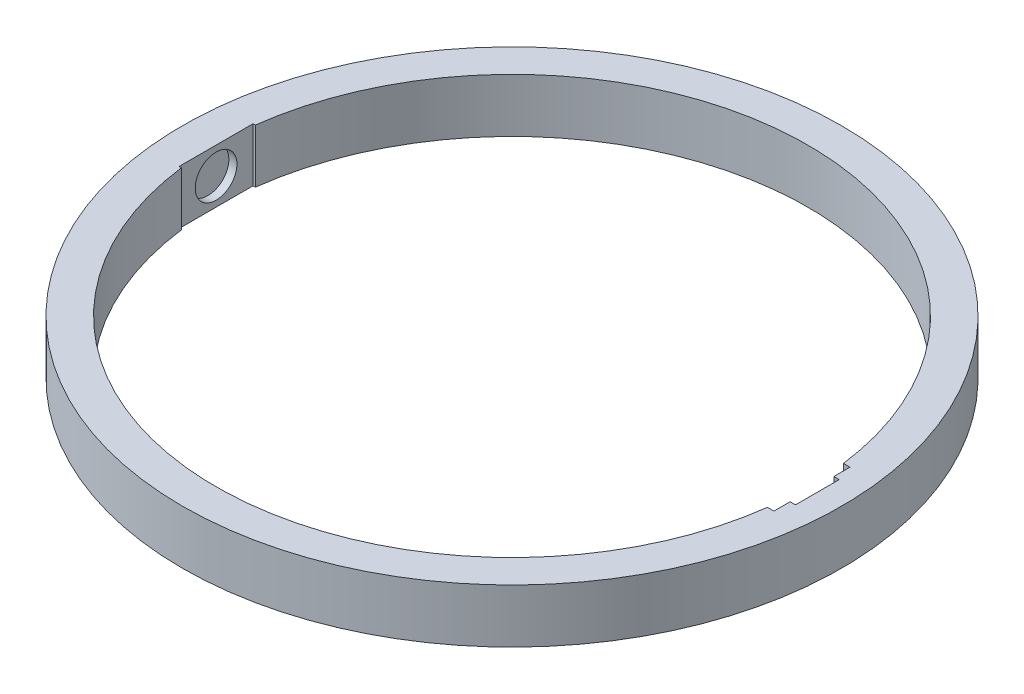
SolidWorks part; units mm, degrees
ref_plane "Front Plane" through (0, 0, 0) normal (0, 0, 1) x (1, 0, 0)
ref_plane "Top Plane" through (0, 0, 0) normal (0, 1, 0) x (1, 0, 0)
ref_plane "Right Plane" through (0, 0, 0) normal (1, 0, 0) x (0, 0, -1)
sketch "Sketch1" plane through (0, 0, 0) normal (0, 1, 0) x (1, 0, 0)
  circle A0 centre (0, 0) radius 440
  circle A1 centre (0, 0) radius 490
  dimension "D1" = 880
  dimension "D2" = 980
extrude "Boss-Extrude1" add sketch "Sketch1" along normal blind 80
sketch "Sketch2" plane through (0, 80, 0) normal (0, 1, 0) x (1, 0, 0)
  line L0 (490, 0) -> (440, 0) construction
  line L1 (530, 55) -> (480, 55)
  line L2 (480, 55) -> (480, -55)
  line L3 (480, -55) -> (530, -55)
  line L4 (530, -55) -> (530, 55)
  circle A0 centre (0, 0) radius 490 construction
  circle A1 centre (0, 0) radius 440 construction
  point P9 (480, 0)
  dimension "D1" = 110
  dimension "D2" = 10
  dimension "D3" = 50
extrude "Cut-Extrude1" [suppressed] cut sketch "Sketch2" against normal through all both and the other way through all
sketch "Sketch3" plane through (0, 80, 0) normal (0, 1, 0) x (1, 0, 0)
  line L0 (446, 32.5) -> (454, 32.5)
  line L1 (454, 32.5) -> (454, -32.5)
  line L2 (454, -32.5) -> (446, -32.5)
  line L3 (446, -32.5) -> (446, -56.5)
  line L4 (446, -56.5) -> (366.03, -56.5)
  line L5 (366.03, -56.5) -> (366.03, 56.5)
  line L6 (366.03, 56.5) -> (446, 56.5)
  line L7 (446, 56.5) -> (446, 32.5)
  line L8 (0, 0) -> (490, 0) construction
  circle A0 centre (0, 0) radius 490 construction
  point P2 (366.03, 0)
  point P12 (490, 0)
  dimension "D1" = 113
  dimension "D2" = 65
  dimension "D3" = 8
  dimension "D4" = 79.97
  dimension "D5" = 36
extrude "Cut-Extrude2" cut sketch "Sketch3" against normal through all both and the other way through all
ref_plane "Plane1" through (-440, 0, 0) normal (1, 0, 0) x (0, 0, -1)
sketch "Sketch4" plane through (-440, 0, 0) normal (1, 0, 0) x (0, 0, -1)
  line L0 (-55, 0) -> (55, 0)
  line L1 (-490, 0) -> (490, 0) construction
  line L2 (55, 0) -> (55, 80)
  line L3 (440, 80) -> (-440, 80) construction
  line L4 (55, 80) -> (-55, 80)
  line L5 (-55, 80) -> (-55, 0)
  point P6 (0, 0)
  dimension "D1" = 110
extrude "Cut-Extrude3" cut sketch "Sketch4" along normal blind 10
sketch "Sketch5" plane through (-440, 0, 0) normal (1, 0, 0) x (0, 0, -1)
  line L0 (0, 80) -> (0, 0) construction
  line L1 (55, 80) -> (-55, 80) construction
  line L2 (-55, 0) -> (55, 0) construction
  circle A0 centre (0, 40) radius 31
  dimension "D1" = 62
extrude "Cut-Extrude4" cut sketch "Sketch5" against normal blind 12
ref_plane "Plane2" through (0, 40, 0) normal (0, 1, 0) x (1, 0, 0)
sketch "Sketch6" plane through (0, 40, 0) normal (0, 1, 0) x (1, 0, 0)
  line L0 (-490, 0) -> (490, 0) construction
  circle A0 centre (0, 0) radius 490 construction
sketch "Sketch7" plane through (0, 80, 0) normal (0, 1, 0) x (1, 0, 0)
  circle A0 centre (0, 0) radius 465 construction
  dimension "D1" = 930
sketch "Sketch8" plane through (0, 0, 0) normal (0, -1, 0) x (1, 0, 0)
  line L0 (-465, 0) -> (465, 0)
  line L1 (-328.8047, -328.8047) -> (328.8047, 328.8047)
  circle A0 centre (0, 0) radius 465 construction
  circle A1 centre (0, 0) radius 465 construction
  dimension "D1" = 45
